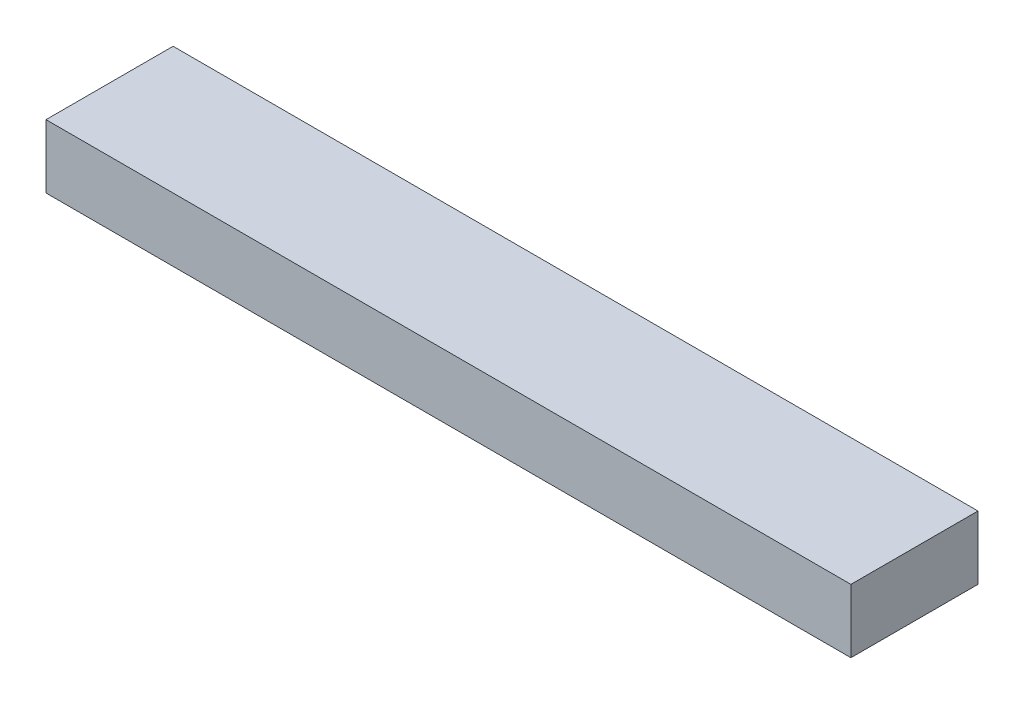
SolidWorks part; units mm, degrees
material "Sapin"
ref_plane "Plan de face" through (0, 0, 0) normal (0, 0, 1) x (1, 0, 0)
ref_plane "Plan de dessus" through (0, 0, 0) normal (0, 1, 0) x (1, 0, 0)
ref_plane "Plan de droite" through (0, 0, 0) normal (1, 0, 0) x (0, 0, -1)
sketch "Esquisse1" plane through (0, 0, 0) normal (0, 1, 0) x (1, 0, 0)
  line L1 (-152, -24) -> (152, -24)
  line L2 (-152, -24) -> (-152, 24)
  line L3 (-152, 24) -> (152, 24)
  line L4 (152, -24) -> (152, 24)
  line L5 (-152, -24) -> (152, 24) construction
  line L6 (-152, 24) -> (152, -24) construction
  point P0 (0, 0)
  dimension "D1" = 304
  dimension "D2" = 48
extrude "Boss.-Extru.1" add sketch "Esquisse1" along normal blind 24
sketch "Esquisse2" plane through (0, 24, 0) normal (0, 1, 0) x (1, 0, 0)
  circle A0 centre (0, 0) radius 4.5
  dimension "D1" = 9
extrude "Enlèv. mat.-Extru.1" [suppressed] cut sketch "Esquisse2" against normal through all
sketch "Esquisse3" [suppressed] plane through (0, 0, 0) normal (0, -1, 0) x (1, 0, 0)
  circle A0 centre (0, 0) radius 7
  dimension "D1" = 14
extrude "Enlèv. mat.-Extru.2" [suppressed] cut sketch "Esquisse3" against normal blind 12
